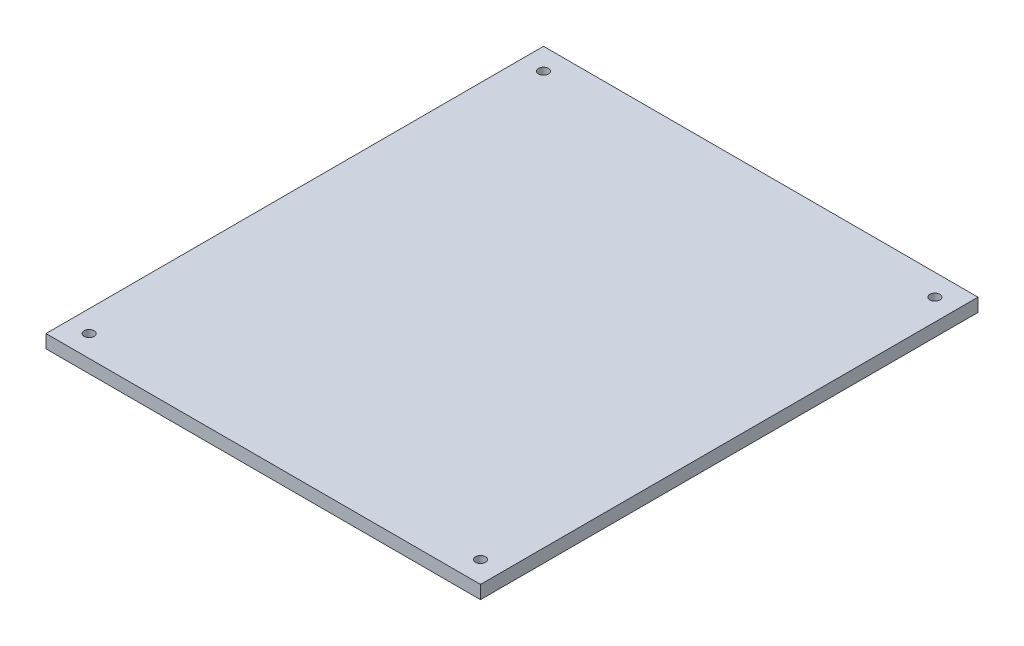
SolidWorks part; units mm, degrees
ref_plane "Front Plane" through (0, 0, 0) normal (0, 0, 1) x (1, 0, 0)
ref_plane "Top Plane" through (0, 0, 0) normal (0, 1, 0) x (1, 0, 0)
ref_plane "Right Plane" through (0, 0, 0) normal (1, 0, 0) x (0, 0, -1)
sketch "Sketch1" plane through (0, 0, 0) normal (0, 1, 0) x (1, 0, 0)
  line L0 (0, 0) -> (0, 75) construction
  line L1 (-65.5, 75) -> (65.5, 75)
  line L2 (-65.5, 75) -> (-65.5, -75)
  line L3 (-65.5, -75) -> (65.5, -75)
  line L4 (65.5, 75) -> (65.5, -75)
  line L5 (0, 0) -> (-65.5, 0) construction
  circle A8 centre (-59, 68.5) radius 1.5
  circle A9 centre (59, 68.5) radius 1.5
  circle A10 centre (59, -68.5) radius 1.5
  circle A11 centre (-59, -68.5) radius 1.5
  point P4 (0, 75)
  point P6 (-65.5, 0)
  dimension "D3" = 6.5
  dimension "D4" = 3
  dimension "D1" = 131
  dimension "D2" = 6.5
  dimension "D7" = 150
extrude "Boss-Extrude1" add sketch "Sketch1" along normal blind 4
